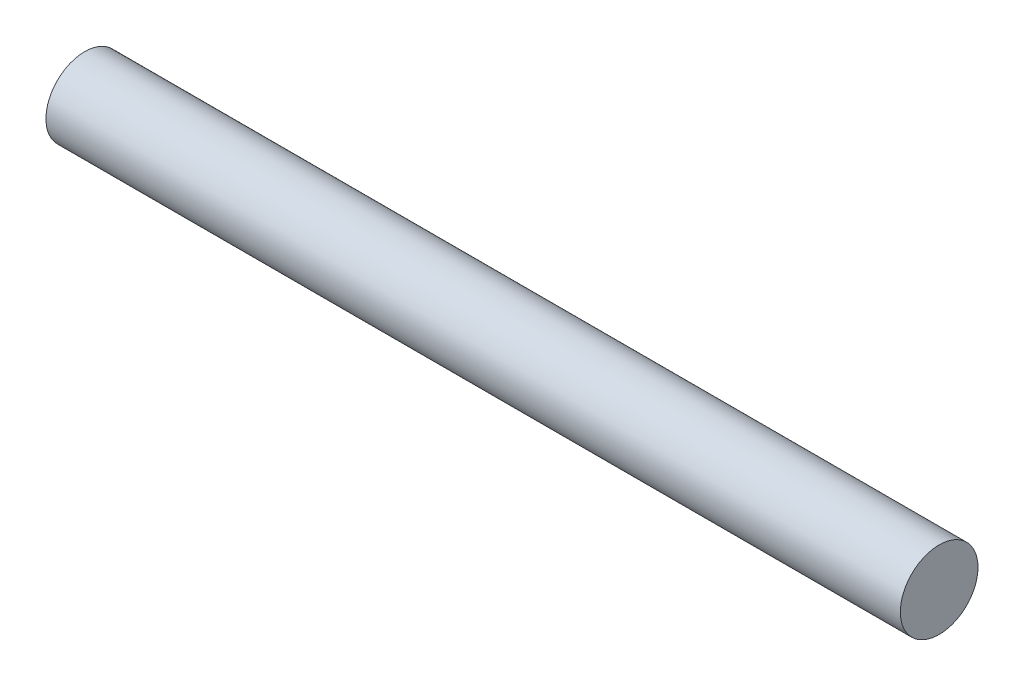
SolidWorks part; units mm, degrees
material "Brass"
ref_plane "Front Plane" through (0, 0, 0) normal (0, 0, 1) x (1, 0, 0)
ref_plane "Top Plane" through (0, 0, 0) normal (0, 1, 0) x (1, 0, 0)
ref_plane "Right Plane" through (0, 0, 0) normal (1, 0, 0) x (0, 0, -1)
sketch "Sketch1" plane through (0, 0, 0) normal (1, 0, 0) x (0, 0, -1)
  circle A0 centre (0, 0) radius 3.175
  dimension "D1" = 6.35
extrude "Boss-Extrude1" add sketch "Sketch1" along normal blind 69.85
